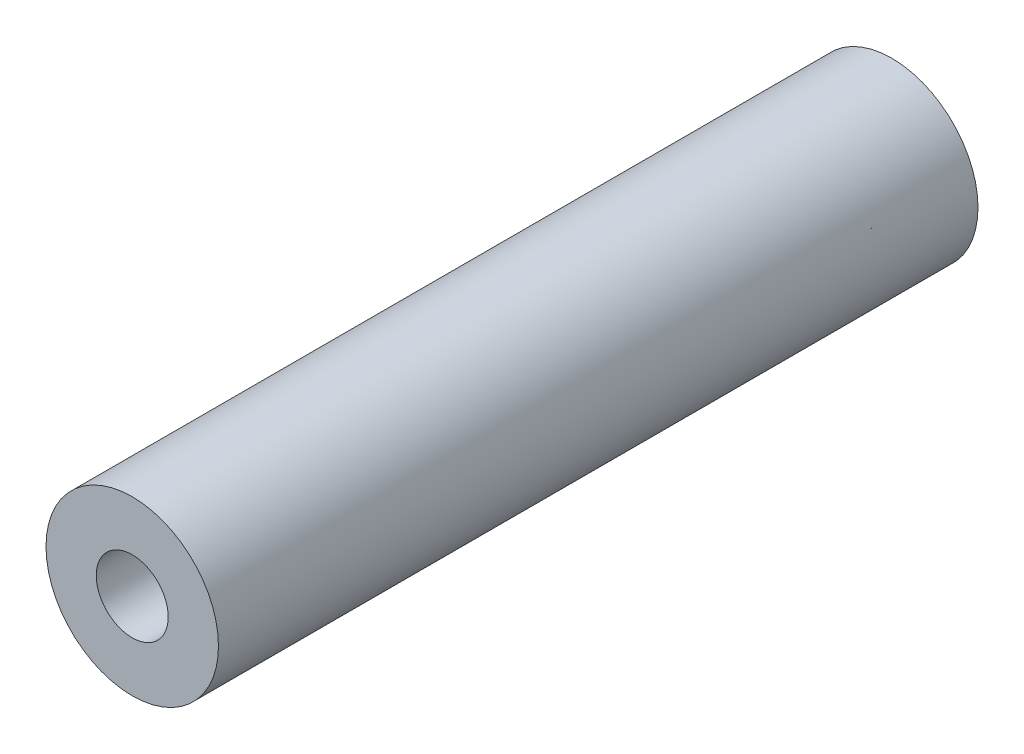
SolidWorks part; units mm, degrees
ref_plane "Front Plane" through (0, 0, 0) normal (0, 0, 1) x (1, 0, 0)
ref_plane "Top Plane" through (0, 0, 0) normal (0, 1, 0) x (1, 0, 0)
ref_plane "Right Plane" through (0, 0, 0) normal (1, 0, 0) x (0, 0, -1)
sketch "Sketch1" plane through (0, 0, 0) normal (0, 0, 1) x (1, 0, 0)
  circle A0 centre (0, 0) radius 9.525
  circle A3 centre (0, 0) radius 3.9751 construction
  circle A4 centre (0, 0) radius 3.9751
  dimension "D1" = 19.05
extrude "Boss-Extrude1" add sketch "Sketch1" against normal up to surface (83.8962 mm away)
